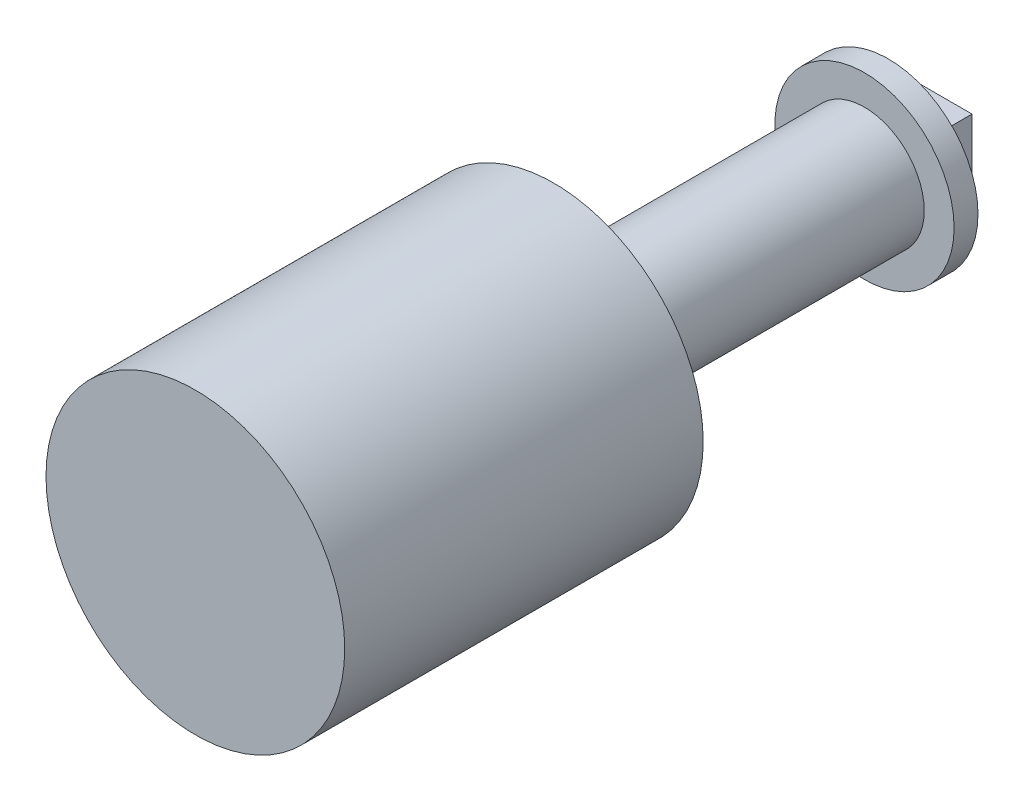
SolidWorks part; units mm, degrees
ref_plane "前视基准面" through (0, 0, 0) normal (0, 0, 1) x (1, 0, 0)
ref_plane "上视基准面" through (0, 0, 0) normal (0, 1, 0) x (1, 0, 0)
ref_plane "右视基准面" through (0, 0, 0) normal (1, 0, 0) x (0, 0, -1)
sketch "草图1" plane through (0, 0, 0) normal (0, 0, 1) x (1, 0, 0)
  circle A0 centre (0, 0) radius 12.5
extrude "凸台-拉伸1" add sketch "草图1" along normal blind 30
sketch "草图4" plane through (0, 0, 0) normal (0, 0, -1) x (-1, 0, 0)
  line L0 (-1000, 0) -> (49000, 0) construction
  line L1 (0, -1000) -> (0, 49000) construction
  circle A0 centre (-8.5, 0) radius 1.5
  circle A1 centre (8.5, 0) radius 1.5
  dimension "D1" = 3
  dimension "D2" = 8.5
extrude "切除-拉伸1" cut sketch "草图4" against normal blind 0.5
sketch "草图2" plane through (0, 0, 0) normal (0, 1, 0) x (1, 0, 0)
  line L0 (0, -1000) -> (0, 49000) construction
  line L1 (12.5, 0) -> (-12.5, 0) construction
  line L2 (0, 28) -> (0, 0)
  line L5 (0, 0) -> (0.75, 0)
  line L6 (0.75, 5) -> (0.75, 0)
  line L7 (0, 2.5) -> (0.75, 0) construction
  line L8 (0, 2.5) -> (0.75, 5) construction
  line L9 (0, 28) -> (5, 28)
  line L11 (0.75, 5) -> (5, 5)
  line L18 (7.5, 26) -> (7.5, 28)
  line L19 (5, 26) -> (5, 5)
  line L20 (-5, 27.6667) -> (-4.8462, 27.6462) construction
  line L21 (0, 28) -> (7.5, 28)
  line L23 (4.8462, 27.6462) -> (5, 27.6667) construction
  line L24 (5, 26) -> (7.5, 26)
  point P1 (0, 2.5)
  point P5 (0, 0)
  point P10 (0, 16.5)
  point P17 (0, 27)
  dimension "D2" = 5
  dimension "D3" = 23
revolve "旋转2" add sketch "草图2" angle 360 about L0
sketch "草图3" plane through (0, 0, -28) normal (0, 0, -1) x (-1, 0, 0)
  line L1 (-3, 3) -> (3, 3)
  line L2 (-3, 3) -> (-3, -3)
  line L3 (-3, -3) -> (3, -3)
  line L4 (3, 3) -> (3, -3)
  line L5 (-3, 3) -> (3, -3) construction
  line L6 (-3, -3) -> (3, 3) construction
  point P0 (0, 0)
  dimension "D1" = 6
  dimension "D2" = 6
extrude "凸台-拉伸2" add sketch "草图3" along normal blind 4
